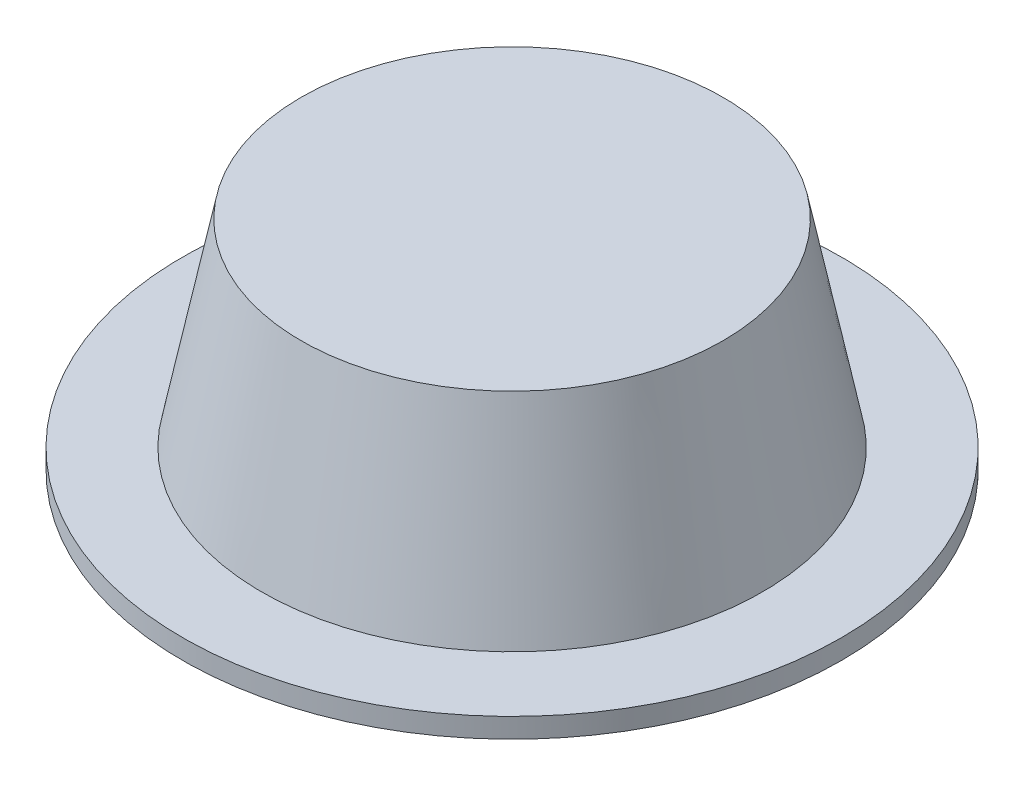
SolidWorks part; units mm, degrees
ref_plane "Front Plane" through (0, 0, 0) normal (0, 0, 1) x (1, 0, 0)
ref_plane "Top Plane" through (0, 0, 0) normal (0, 1, 0) x (1, 0, 0)
ref_plane "Right Plane" through (0, 0, 0) normal (1, 0, 0) x (0, 0, -1)
sketch "Sketch1" plane through (0, 0, 0) normal (0, 0, 1) x (1, 0, 0)
  line L0 (0, 15) -> (0, 0)
  line L1 (0, 0) -> (19, 0)
  line L2 (0, 15) -> (16, 15)
  line L3 (16, 15) -> (19, 0)
  dimension "D3" = 16
  dimension "D1" = 19
  dimension "D2" = 15
revolve "Revolve1" add sketch "Sketch1" angle 360 about L0
shell "Shell1" thickness 3
sketch "Sketch2" plane through (0, 0, 0) normal (0, -1, 0) x (1, 0, 0)
  circle A2 centre (0, 0) radius 25
  circle A5 centre (0, 0) radius 15.9406 construction
  circle A6 centre (0, 0) radius 15.9406
  dimension "D1" = 50
extrude "Boss-Extrude1" add sketch "Sketch2" along normal blind 1.5 separate body
sketch "Sketch4" [suppressed] plane through (0, 0, 0) normal (0, -1, 0) x (1, 0, 0)
  circle A0 centre (0, 0) radius 15.7834 construction
  circle A1 centre (0, 0) radius 19
  circle A3 centre (0, 0) radius 15.7834
  circle A5 centre (0, 0) radius 19
  dimension "D1" = 0
extrude "Boss-Extrude2" [suppressed] add sketch "Sketch4" along normal blind 2
sketch "Sketch5" plane through (0, 12, 0) normal (0, -1, 0) x (1, 0, 0)
  line L1 (-2, 6) -> (2, 6)
  line L2 (-2, 6) -> (-2, -6)
  line L3 (-2, -6) -> (2, -6)
  line L4 (2, 6) -> (2, -6)
  point P5 (0, 6)
  point P6 (2, 0)
  dimension "D1" = 12
  dimension "D2" = 4
extrude "Boss-Extrude3" add sketch "Sketch5" along normal blind 11
